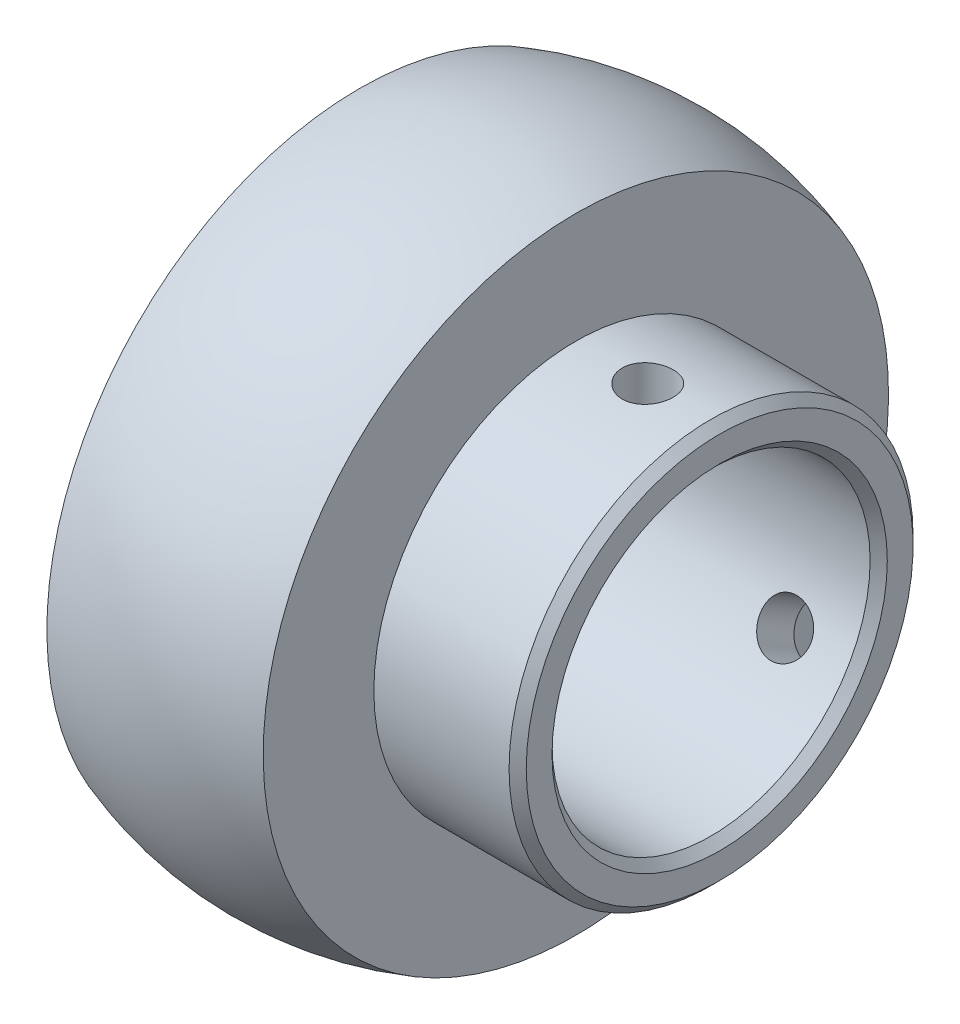
SolidWorks part; units mm, degrees
material "AISI 1020"
ref_plane "Спереди" through (0, 0, 0) normal (0, 0, 1) x (1, 0, 0)
ref_plane "Сверху" through (0, 0, 0) normal (0, 1, 0) x (1, 0, 0)
ref_plane "Справа" through (0, 0, 0) normal (1, 0, 0) x (0, 0, -1)
sketch "Эскиз1" plane through (0, 0, 0) normal (0, 0, 1) x (1, 0, 0)
  line L0 (-1000, 0) -> (49000, 0) construction
  line L1 (-8.5, 24.5713) -> (-8.5, 15.875)
  line L2 (-14.3, 12.5) -> (19.8, 12.5)
  line L3 (-14.3, 12.5) -> (-14.3, 15.875)
  line L4 (-14.3, 15.875) -> (-8.5, 15.875)
  line L5 (19.8, 12.5) -> (19.8, 15.875)
  line L6 (8.5, 24.5713) -> (8.5, 15.875)
  line L7 (8.5, 15.875) -> (19.8, 15.875)
  line L8 (-14.3, 15.875) -> (-14.3, 19.25) construction
  line L9 (-14.3, 19.25) -> (-14.3, 22.625) construction
  line L10 (-14.3, 22.625) -> (-14.3, 26) construction
  line L11 (-14.3, 26) -> (0, 26) construction
  line L12 (-3.9, 0) -> (-3.9, 25.7058) construction
  arc A0 (-8.5, 24.5713) -> (8.5, 24.5713) centre (0, 0) cw
  point P10 (0, 26)
  dimension "_B" = 34.1
  dimension "_S" = 14.3
  dimension "_C" = 17
  dimension "_D" = 52
  dimension "_d_" = 25
  dimension "_Ca" = 3.9
  dimension "Z" = 3.375
revolve "Повернуть1" add sketch "Эскиз1" angle 360 about L0
sketch "Эскиз2" plane through (0, 0, 0) normal (0, 1, 0) x (1, 0, 0)
  line L0 (-201000, 0) -> (249000, 0) construction
  line L1 (8.5, 0) -> (19.8, 0) construction
  circle A0 centre (14.15, 0) radius 2
  point P6 (14.15, 0)
  dimension "D1" = 4
extrude "Вырез-Вытянуть1" cut sketch "Эскиз2" along normal through all
pattern_circular "Круговой массив1" count 2 over 120 about axis through (-1000, 0, 0) along (-1, 0, 0) of "Вырез-Вытянуть1"
chamfer "Фаска1" distance 0.675 angle 45 4 edges at (19.8, 0, 12.5) (19.8, 0, 15.875) (-14.3, 0, 15.875) (-14.3, 0, 12.5)
equation "\"D1@Фаска1\"= \"Z@Эскиз1\" / 5"
